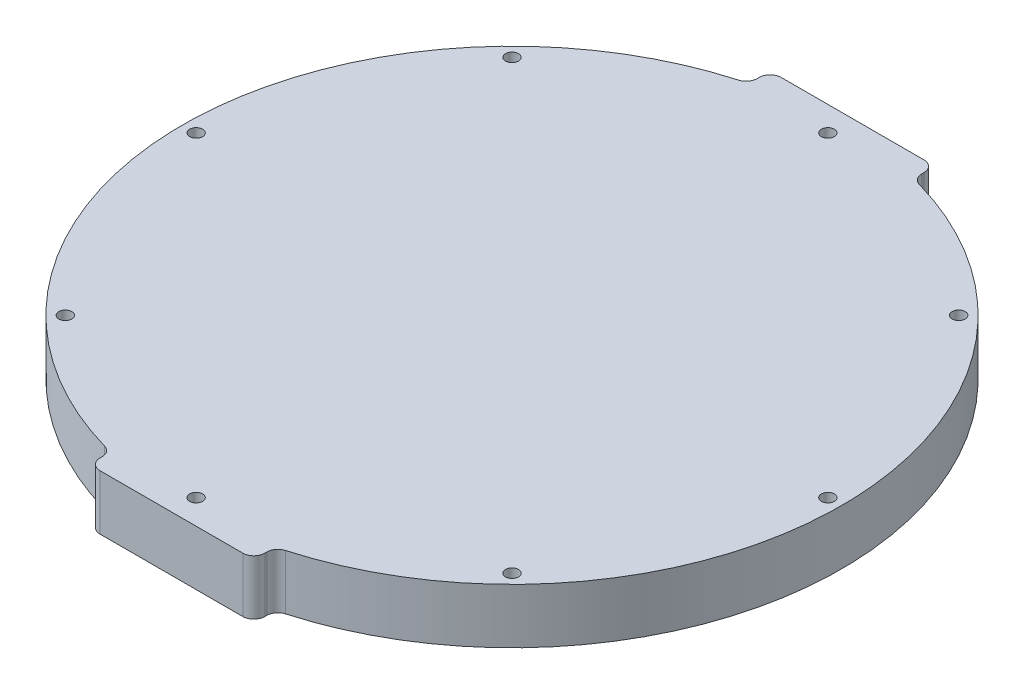
SolidWorks part; units mm, degrees
material "6061 Alloy"
ref_plane "Front Plane" through (0, 0, 0) normal (0, 0, 1) x (1, 0, 0)
ref_plane "Top Plane" through (0, 0, 0) normal (0, 1, 0) x (1, 0, 0)
ref_plane "Right Plane" through (0, 0, 0) normal (1, 0, 0) x (0, 0, -1)
sketch "Sketch2" plane through (0, 0, 0) normal (0, 1, 0) x (1, 0, 0)
  circle A0 centre (0, 0) radius 76.2
extrude "Boss-Extrude1" add sketch "Sketch2" along normal blind 12.7
sketch "Sketch3" plane through (0, 0, 0) normal (0, 0, 1) x (1, 0, 0)
  line L0 (0, 0) -> (-19.05, 0)
  line L1 (-19.05, 0) -> (-19.05, 12.7)
  line L2 (-19.05, 12.7) -> (19.05, 12.7)
  line L3 (19.05, 12.7) -> (19.05, 0)
  line L4 (0, 0) -> (19.05, 0)
extrude "Boss-Extrude2" add sketch "Sketch3" along normal blind 78.74 and the other way blind 78.74
fillet "Fillet1" radius 2.54 8 edges at (19.05, 6.35, 73.7803) (19.05, 6.35, -73.7803) (19.05, 6.35, 78.74) (-19.05, 6.35, -73.7803) (-19.05, 6.35, 73.7803) (-19.05, 6.35, 78.74) (-19.05, 6.35, -78.74) (19.05, 6.35, -78.74)
sketch "Sketch4" plane through (0, 12.7, 0) normal (0, 1, 0) x (1, 0, 0)
  circle A0 centre (73.025, 0) radius 1.5011
  circle A1 centre (51.6365, -51.6365) radius 1.5011
  circle A2 centre (0, -73.025) radius 1.5011
  circle A3 centre (-51.6365, -51.6365) radius 1.5011
  circle A4 centre (-73.025, 0) radius 1.5011
  circle A5 centre (-51.6365, 51.6365) radius 1.5011
  circle A6 centre (0, 73.025) radius 1.5011
  circle A7 centre (51.6365, 51.6365) radius 1.5011
  point P18 (0, 0)
  dimension "D1" = 8
extrude "Cut-Extrude1" cut sketch "Sketch4" against normal through all
